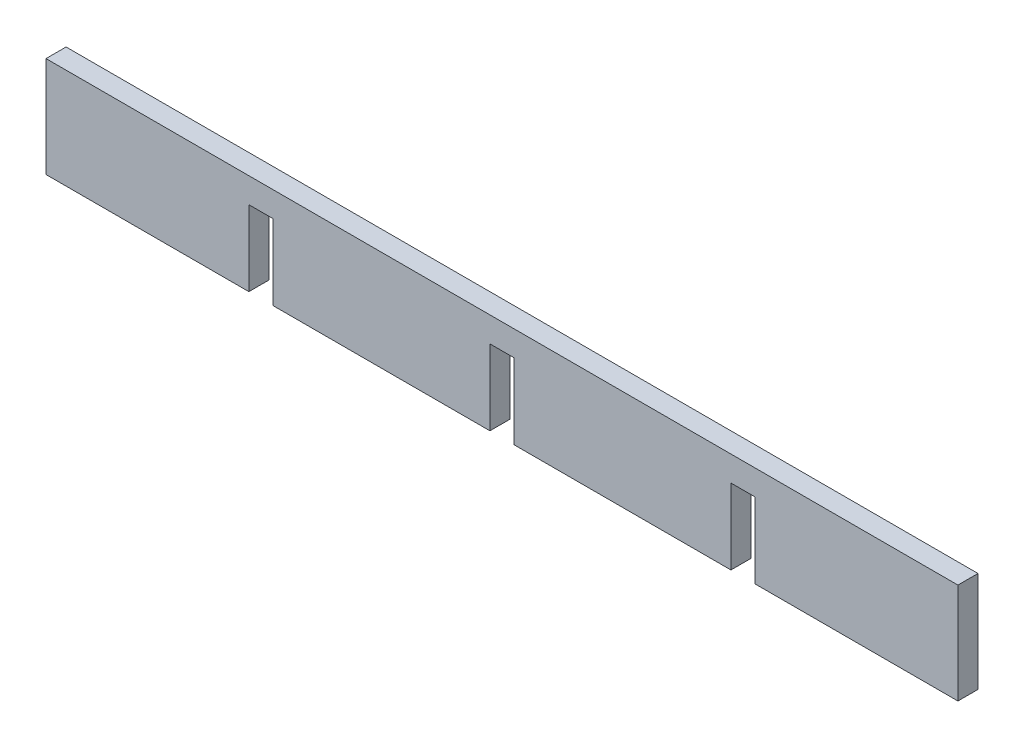
SolidWorks part; units mm, degrees
ref_plane "Front Plane" through (0, 0, 0) normal (0, 0, 1) x (1, 0, 0)
ref_plane "Top Plane" through (0, 0, 0) normal (0, 1, 0) x (1, 0, 0)
ref_plane "Right Plane" through (0, 0, 0) normal (1, 0, 0) x (0, 0, -1)
sketch "Sketch1" plane through (0, 0, 0) normal (0, 0, 1) x (1, 0, 0)
  line B0 (-216.535, 0) -> (-147.955, 0)
  line B1 (-147.955, 0) -> (-147.955, 23.8125)
  line B2 (-147.955, 23.8125) -> (-140.335, 23.8125)
  line B3 (-140.335, 23.8125) -> (-140.335, 0)
  line B4 (-140.335, 0) -> (-71.755, 0)
  line B5 (-71.755, 0) -> (-71.755, 23.8125)
  line B6 (-71.755, 23.8125) -> (-64.135, 23.8125)
  line B7 (-64.135, 23.8125) -> (-64.135, 0)
  line B8 (-64.135, 0) -> (0, 0)
  line B9 (0, 0) -> (0, 31.75)
  line B10 (0, 31.75) -> (-288.29, 31.75)
  line B11 (-288.29, 31.75) -> (-288.29, 0)
  line B12 (-288.29, 0) -> (-224.155, 0)
  line B13 (-224.155, 0) -> (-224.155, 23.8125)
  line B14 (-224.155, 23.8125) -> (-216.535, 23.8125)
  line B15 (-216.535, 23.8125) -> (-216.535, 0)
sketch_block_instance "Sidewall-1"
sketch_block "Sidewall"
extrude "Boss-Extrude1" add sketch "Sketch1" along normal blind 6.35
